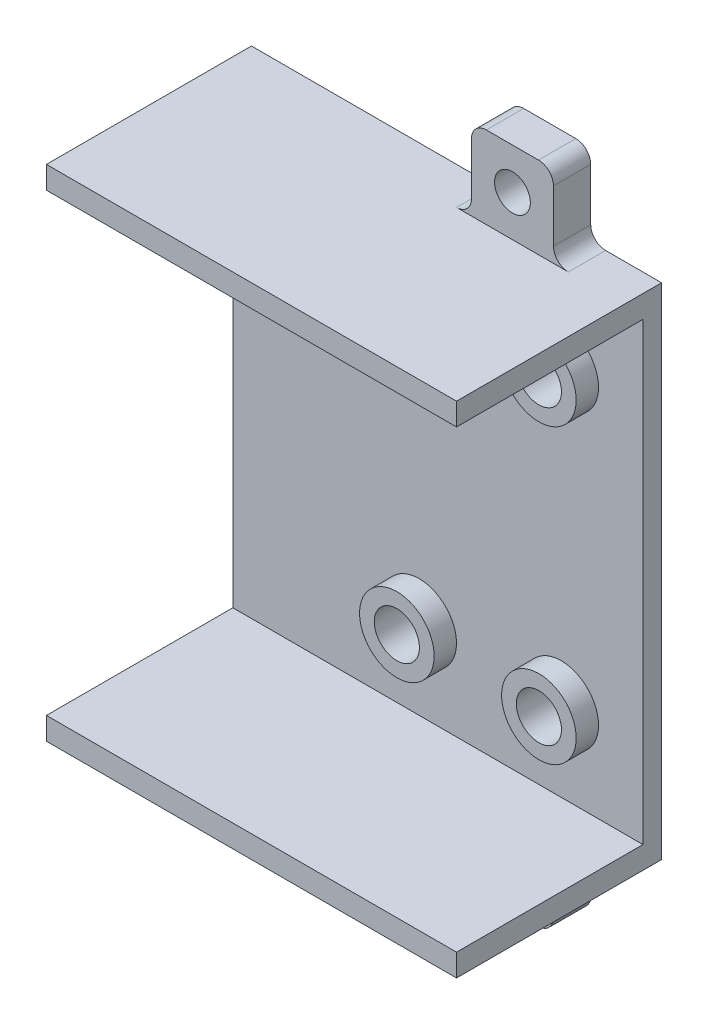
SolidWorks part; units mm, degrees
material "ABS"
ref_plane "X-Y Datum" through (0, 0, 0) normal (0, 0, 1) x (1, 0, 0)
ref_plane "X-Z Datum" through (0, 0, 0) normal (0, 1, 0) x (1, 0, 0)
ref_plane "Y-Z Datum" through (0, 0, 0) normal (1, 0, 0) x (0, 0, -1)
sketch "Sketch1" plane through (0, 0, 0) normal (0, 0, 1) x (1, 0, 0)
  line L1 (-27.5, 33.5) -> (27.5, 33.5)
  line L2 (-27.5, 33.5) -> (-27.5, -33.5)
  line L3 (-27.5, -33.5) -> (27.5, -33.5)
  line L4 (27.5, 33.5) -> (27.5, -33.5)
  line L5 (-27.5, 33.5) -> (27.5, -33.5) construction
  line L6 (-27.5, -33.5) -> (27.5, 33.5) construction
  point P0 (0, 0)
  dimension "D1" = 55
  dimension "D2" = 67
extrude "Boss-Extrude1" add sketch "Sketch1" along normal blind 2.5
sketch "Sketch2" plane through (0, 0, 2.5) normal (0, 0, 1) x (1, 0, 0)
  line L0 (27.5, -33.5) -> (27.5, 33.5) construction
  line L1 (-27.5, 33.5) -> (27.5, 33.5)
  line L2 (-27.5, 33.5) -> (-27.5, 30.5)
  line L3 (-27.5, 30.5) -> (27.5, 30.5)
  line L4 (27.5, 33.5) -> (27.5, 30.5)
  line L5 (-27.5, 33.5) -> (-27.5, -33.5) construction
  line L6 (27.5, -33.5) -> (-27.5, -33.5)
  line L7 (27.5, -33.5) -> (27.5, -30.5)
  line L8 (27.5, -30.5) -> (-27.5, -30.5)
  line L9 (-27.5, -33.5) -> (-27.5, -30.5)
  dimension "D1" = 3
extrude "Boss-Extrude2" add sketch "Sketch2" along normal blind 25
sketch "Sketch3" plane through (0, 0, 2.5) normal (0, 0, 1) x (1, 0, 0)
  circle A0 centre (-2.504, 19.6215) radius 3.025
  circle A1 centre (16.546, 19.6215) radius 3.025
  circle A2 centre (16.546, -19.6215) radius 3.025
  circle A3 centre (-2.504, -19.6215) radius 3.025
  circle A4 centre (-2.504, 19.6215) radius 5
  circle A5 centre (16.546, 19.6215) radius 5
  circle A6 centre (16.546, -19.6215) radius 5
  circle A7 centre (-2.504, -19.6215) radius 5
  dimension "D1" = 6.05
  dimension "D2" = 10
extrude "Boss-Extrude3" add sketch "Sketch3" along normal blind 3
sketch "Sketch4" plane through (0, 0, 2.5) normal (0, 0, 1) x (1, 0, 0)
  circle A0 centre (16.546, -19.6215) radius 3.025 construction
  circle A1 centre (-2.504, -19.6215) radius 3.025 construction
  circle A2 centre (16.546, 19.6215) radius 3.025 construction
  circle A3 centre (-2.504, 19.6215) radius 3.025 construction
  circle A4 centre (16.546, -19.6215) radius 3.025
  circle A5 centre (-2.504, -19.6215) radius 3.025
  circle A6 centre (16.546, 19.6215) radius 3.025
  circle A7 centre (-2.504, 19.6215) radius 3.025
extrude "Cut-Extrude1" cut sketch "Sketch4" against normal blind 2
sketch "Sketch5" plane through (0, 0, 0) normal (0, 0, -1) x (-1, 0, 0)
  line L0 (-27.5, 33.5) -> (27.5, 33.5) construction
  line L1 (-18, 33.5) -> (-7, 33.5)
  line L2 (-18, 33.5) -> (-18, 44.5)
  line L3 (-18, 44.5) -> (-7, 44.5)
  line L4 (-7, 33.5) -> (-7, 44.5)
  line L5 (-12.5, 44.5) -> (-12.5, 33.5)
  line L6 (-27.5, -33.5) -> (-27.5, 33.5) construction
  circle A0 centre (-12.5, 39) radius 2 construction
  line M9 (27.5, 33.5) -> (-27.5, 33.5)
  dimension "D3" = 4
  dimension "D1" = 11
  dimension "D2" = 11
  dimension "D4" = 15
extrude "Boss-Extrude4" add sketch "Sketch5" against normal blind 5 contours L3 L5 L4 M9 | L5 L3 L2 L1
hole_wizard "M4 Clearance Hole1" positions "Sketch8" profile "Sketch7" hole size "M4" standard "ANSI Metric" end condition through all
sketch "Sketch8" plane through (0, 0, 5) normal (0, 0, 1) x (1, 0, 0)
  point P0 (12.5, 39)
sketch "Sketch7" plane through (12.5, 39, 5) normal (1, 0, 0) x (0, -1, 0)
  line L0 (0, 0) -> (0, 5)
  line L1 (0, 5) -> (2.4, 5)
  line L2 (2.4, 5) -> (2.4, 0)
  line L5 (2.4, 0) -> (0, 0)
  line L11 (0, -6.35) -> (0, 107.95) construction
  dimension "Thru Hole Dia." = 4.8
  dimension "Thru Hole Depth" = 5
sketch "Sketch9" plane through (0, 0, 5) normal (0, 0, 1) x (1, 0, 0)
  line L0 (12.5, 41.4) -> (18, 41.4)
  line L1 (12.5, 44.5) -> (12.5, 33.5) construction
  line L2 (18, 33.5) -> (18, 44.5) construction
  line L3 (12.5, 36.6) -> (18, 36.6)
  line L8 (18, 44.5) -> (7, 44.5)
  line L9 (7, 44.5) -> (7, 33.5)
  line L10 (7, 33.5) -> (18, 33.5)
  line L11 (18, 33.5) -> (18, 44.5)
  line L12 (18, 44.5) -> (7, 44.5)
  line L13 (7, 44.5) -> (7, 33.5)
  line L14 (7, 33.5) -> (18, 33.5)
  line L15 (18, 33.5) -> (18, 44.5)
  circle A0 centre (12.5, 39) radius 2.4 construction
  circle A1 centre (12.5, 39) radius 2.4
  circle M5 centre (12.5, 39) radius 2.4
  line M9 (18, 33.5) -> (18, 44.5)
  dimension "D1" = 0
extrude "Cut-Extrude2" [suppressed] cut sketch "Sketch9" against normal through all contours L3 L0 M5 M9
mirror "Mirror2" about plane through (0, 0, 0) normal (0, 1, 0) of "Cut-Extrude2", "M4 Clearance Hole1", "Boss-Extrude4"
fillet "Fillet2" [suppressed] radius 2
fillet "Fillet3" radius 2 8 edges at (18, -33.5, 2.5) (18, -44.5, 2.5) (7, -44.5, 2.5) (7, -33.5, 2.5) (18, 33.5, 2.5) (18, 44.5, 2.5) (7, 44.5, 2.5) (7, 33.5, 2.5)
